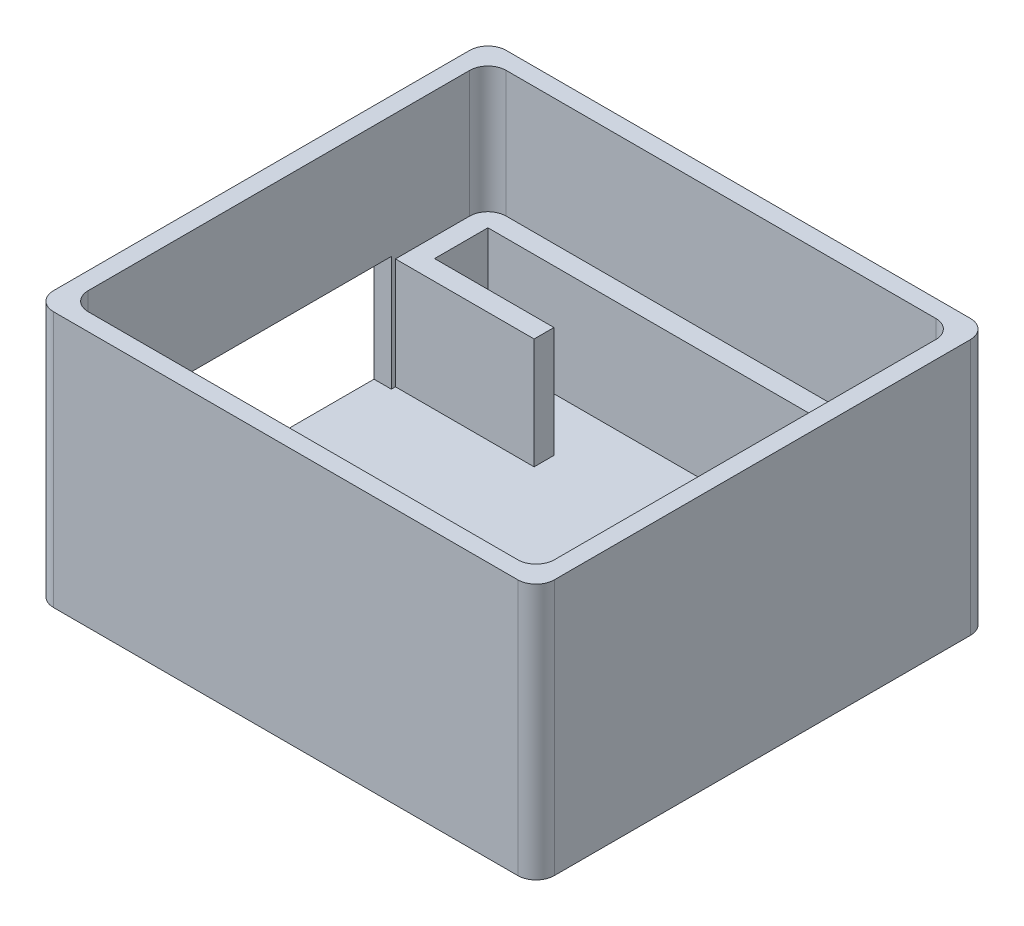
SolidWorks part; units mm, degrees
ref_plane "前视基准面" through (0, 0, 0) normal (0, 0, 1) x (1, 0, 0)
ref_plane "上视基准面" through (0, 0, 0) normal (0, 1, 0) x (1, 0, 0)
ref_plane "右视基准面" through (0, 0, 0) normal (1, 0, 0) x (0, 0, -1)
sketch "草图1" plane through (0, 0, 0) normal (0, 1, 0) x (1, 0, 0)
  line L0 (0, 21.5) -> (0, 22.5) construction
  line L1 (0, 0) -> (24, 0)
  line L2 (0, 0) -> (0, 21.5)
  line L3 (0, 21.5) -> (24, 21.5)
  line L4 (24, 0) -> (24, 21.5)
  line L5 (0, 22.5) -> (-1, 22.5) construction
  line L6 (24, 0) -> (24, -1) construction
  line L7 (24, -1) -> (25, -1) construction
  line L9 (-1, 22.5) -> (25, 22.5)
  line L10 (-1, 22.5) -> (-1, -1)
  line L11 (-1, -1) -> (25, -1)
  line L12 (25, 22.5) -> (25, -1)
  dimension "D1" = 1
extrude "凸台-拉伸1" add sketch "草图1" along normal blind 10
sketch "草图2" plane through (-1, 0, 0) normal (-1, 0, 0) x (0, 0, 1)
  line L0 (-16.5866, 0) -> (-16.5866, 3.6693) construction
  line L1 (-22.5, 0) -> (1, 0) construction
  line L2 (-16.5866, 3.6693) -> (-4.0819, 0) construction
  line L3 (-4.0819, 0) -> (-4.0819, 3.6693) construction
  line L5 (-16.5866, 0) -> (-4.0819, 0)
  line L6 (-16.5866, 0) -> (-16.5866, 3.6693)
  line L7 (-16.5866, 3.6693) -> (-4.0819, 3.6693)
  line L8 (-4.0819, 0) -> (-4.0819, 3.6693)
extrude "切除-拉伸1" cut sketch "草图2" against normal blind 1
sketch "草图3" plane through (0, 0, 0) normal (0, -1, 0) x (1, 0, 0)
  line L0 (-1, -4.0819) -> (-1, 1)
  line L1 (-1, 1) -> (25, 1)
  line L2 (25, 1) -> (25, -22.5)
  line L3 (25, -22.5) -> (-1, -22.5)
  line L4 (-1, -22.5) -> (-1, -16.5866)
  line L5 (-1, -16.5866) -> (0, -16.5866)
  line L6 (0, -16.5866) -> (0, -21.5)
  line L7 (0, -21.5) -> (24, -21.5)
  line L8 (24, -21.5) -> (24, 0)
  line L9 (24, 0) -> (0, 0)
  line L10 (0, 0) -> (0, -4.0819)
  line L11 (0, -4.0819) -> (-1, -4.0819)
extrude "凸台-拉伸2" add sketch "草图3" along normal blind 2.3
sketch "草图5" plane through (0, -2.3, 0) normal (0, -1, 0) x (1, 0, 0)
  line L1 (-1, 1) -> (25, 1)
  line L2 (-1, 1) -> (-1, -22.5)
  line L3 (-1, -22.5) -> (25, -22.5)
  line L4 (25, 1) -> (25, -22.5)
extrude "凸台-拉伸3" add sketch "草图5" along normal blind 1
sketch "草图6" plane through (0, 10, 0) normal (0, 1, 0) x (1, 0, 0)
  line L0 (0, 21.5) -> (-0.1, 21.5) construction
  line L1 (-0.1, 21.5) -> (-0.1, 21.6) construction
  line L2 (24, 0) -> (24.1, 0) construction
  line L3 (24.1, 0) -> (24.1, -0.1) construction
  line L5 (24, 0) -> (0, 0)
  line L6 (24, 0) -> (24, 21.5)
  line L7 (24, 21.5) -> (0, 21.5)
  line L8 (0, 0) -> (0, 21.5)
  line L9 (-0.1, 21.6) -> (24.1, 21.6)
  line L10 (-0.1, 21.6) -> (-0.1, -0.1)
  line L11 (-0.1, -0.1) -> (24.1, -0.1)
  line L12 (24.1, 21.6) -> (24.1, -0.1)
extrude "切除-拉伸2" cut sketch "草图6" against normal up to surface (12.3 mm away) up to face at (5.75, -2.3, -10.5421)
sketch "草图7" plane through (0, -2.3, 0) normal (0, 1, 0) x (1, 0, 0)
  line L1 (-0.1, 21.6) -> (0.9, 21.6)
  line L2 (-0.1, 21.6) -> (-0.1, 20.6)
  line L3 (-0.1, 20.6) -> (0.9, 20.6)
  line L4 (0.9, 21.6) -> (0.9, 20.6)
  line L5 (24.1, 21.6) -> (23.1, 21.6)
  line L6 (24.1, 21.6) -> (24.1, 20.6)
  line L7 (24.1, 20.6) -> (23.1, 20.6)
  line L8 (23.1, 21.6) -> (23.1, 20.6)
  line L9 (24.1, -0.1) -> (23.1, -0.1)
  line L10 (24.1, -0.1) -> (24.1, 0.9)
  line L11 (24.1, 0.9) -> (23.1, 0.9)
  line L12 (23.1, -0.1) -> (23.1, 0.9)
  line L13 (-0.1, -0.1) -> (0.9, -0.1)
  line L14 (-0.1, -0.1) -> (-0.1, 0.9)
  line L15 (-0.1, 0.9) -> (0.9, 0.9)
  line L16 (0.9, -0.1) -> (0.9, 0.9)
  line L17 (0.9, 20.6) -> (23.1, 20.6)
  line L18 (0.9, 20.6) -> (0.9, 21.6)
  line L19 (0.9, 21.6) -> (23.1, 21.6)
  line L20 (23.1, 20.6) -> (23.1, 21.6)
  line L21 (23.1, 20.6) -> (24.1, 20.6)
  line L22 (23.1, 20.6) -> (23.1, 0.9)
  line L23 (23.1, 0.9) -> (24.1, 0.9)
  line L24 (24.1, 20.6) -> (24.1, 0.9)
  line L25 (0.9, 0.9) -> (23.1, 0.9)
  line L26 (0.9, 0.9) -> (0.9, -0.1)
  line L27 (0.9, -0.1) -> (23.1, -0.1)
  line L28 (23.1, 0.9) -> (23.1, -0.1)
  line L29 (0.9, 0.9) -> (-0.1, 0.9)
  line L30 (0.9, 0.9) -> (0.9, 4.0819)
  line L31 (0.9, 4.0819) -> (-0.1, 4.0819)
  line L32 (-0.1, 0.9) -> (-0.1, 4.0819)
  line L33 (-0.1, 20.6) -> (0.9, 20.6)
  line L34 (-0.1, 20.6) -> (-0.1, 16.8)
  line L35 (-0.1, 16.8) -> (0.9, 16.8)
  line L36 (0.9, 20.6) -> (0.9, 16.8)
  line L37 (0.9, 16.8) -> (7.0972, 16.8)
  line L38 (0.9, 16.8) -> (0.9, 17.83)
  line L39 (0.9, 17.83) -> (7.0972, 17.83)
  line L40 (7.0972, 16.8) -> (7.0972, 17.83)
  line L41 (0.9, 4.0819) -> (7.1, 4.0819)
  line L42 (0.9, 4.0819) -> (0.9, 3.0819)
  line L43 (0.9, 3.0819) -> (7.1, 3.0819)
  line L44 (7.1, 4.0819) -> (7.1, 3.0819)
  line M1 (-0.1, 21.6) -> (-0.1, 16.5866)
  line M5 (-0.1, 4.0819) -> (-0.1, -0.1)
  line M6 (-0.1, -0.1) -> (24.1, -0.1)
  line M7 (24.1, -0.1) -> (24.1, 21.6)
  line M8 (24.1, 21.6) -> (-0.1, 21.6)
extrude "凸台-拉伸4" add sketch "草图7" along normal blind 5.75 contours L4 L17 L8 M8 | L4 L3 M8 M1 | L36 L3 L35 M1 | L8 L7 M8 M7 | L7 L22 L11 M7 | L25 L16 L12 M6 | L12 L11 M6 M7 | L16 L15 M6 M5 | L30 L31 L15 M5 | L38 L37 L40 L39 | L42 L41 L44 L43
fillet "圆角1" radius 0.95 8 edges at (25, 3.35, 1) (25, 3.35, -22.5) (-1, 3.35, -22.5) (-1, 3.35, 1) (-0.1, 6.725, 0.1) (24.1, 6.725, 0.1) (24.1, 6.725, -21.6) (-0.1, 6.725, -21.6)
